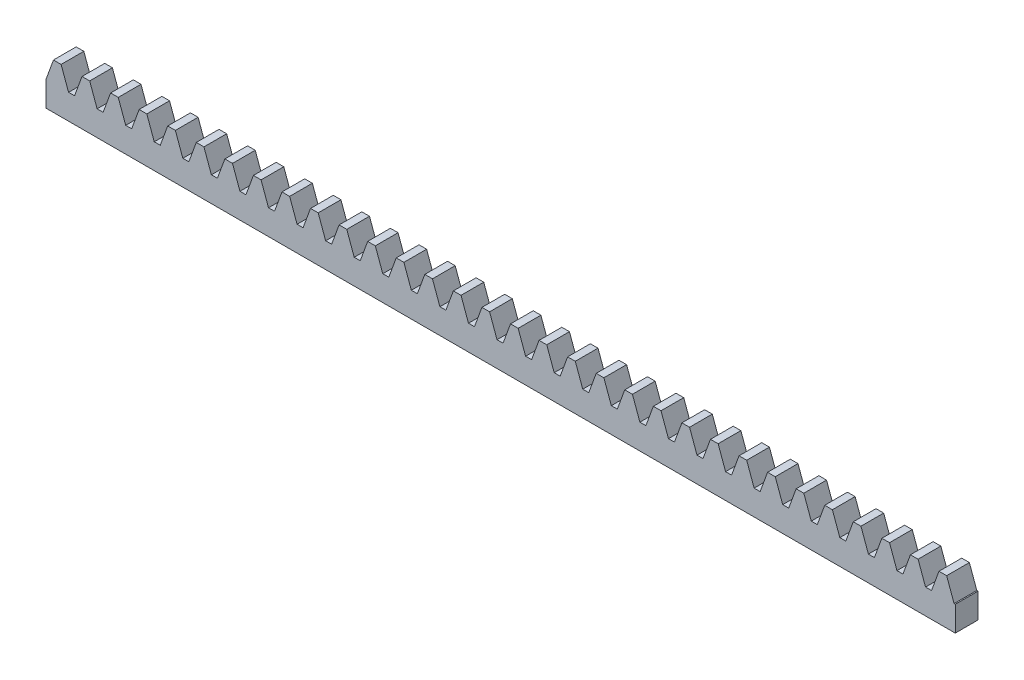
SolidWorks part; units mm, degrees
ref_plane "前视基准面" through (0, 0, 0) normal (0, 0, 1) x (1, 0, 0)
ref_plane "上视基准面" through (0, 0, 0) normal (0, 1, 0) x (1, 0, 0)
ref_plane "右视基准面" through (0, 0, 0) normal (1, 0, 0) x (0, 0, -1)
sketch "草图1" plane through (0, 0, 0) normal (0, 0, 1) x (1, 0, 0)
  line L1 (0, 0) -> (200, 0)
  line L2 (0, 0) -> (0, -5.5)
  line L3 (0, -5.5) -> (200, -5.5)
  line L4 (200, 0) -> (200, -5.5)
  dimension "D1" = 5.5
  dimension "L" = 200
extrude "拉伸1" add sketch "草图1" along normal blind 5
sketch "草图2" plane through (0, 0, 5) normal (0, 0, 1) x (1, 0, 0)
  line L0 (0, 0) -> (1.6379, 4.5)
  line L1 (1.6379, 4.5) -> (3.3236, 4.5)
  line L2 (3.3236, 4.5) -> (4.9614, 0)
  line L3 (200, 0) -> (0, 0) construction
  line L4 (0, 0) -> (4.9614, 0)
  line L5 (0.9099, 2.5) -> (4.0515, 2.5) construction
  dimension "D2" = 70
  dimension "alpha" = 110
  dimension "ha" = 2
  dimension "hf" = 2.5
  dimension "S" = 3.1416
extrude "拉伸2" add sketch "草图2" against normal up to surface (5 mm away) up to face at (100, -2.75, 0)
pattern_linear "阵列(线性)1" count 32 spacing 6.2832 along (1, 0, 0) of "拉伸2"
equation "\"d\"=\"S@草图2\" * 2"
equation "\"z\"= int(  \"L@草图1\" / (  \"S@草图2\" * 2 ) + 0.5 )"
